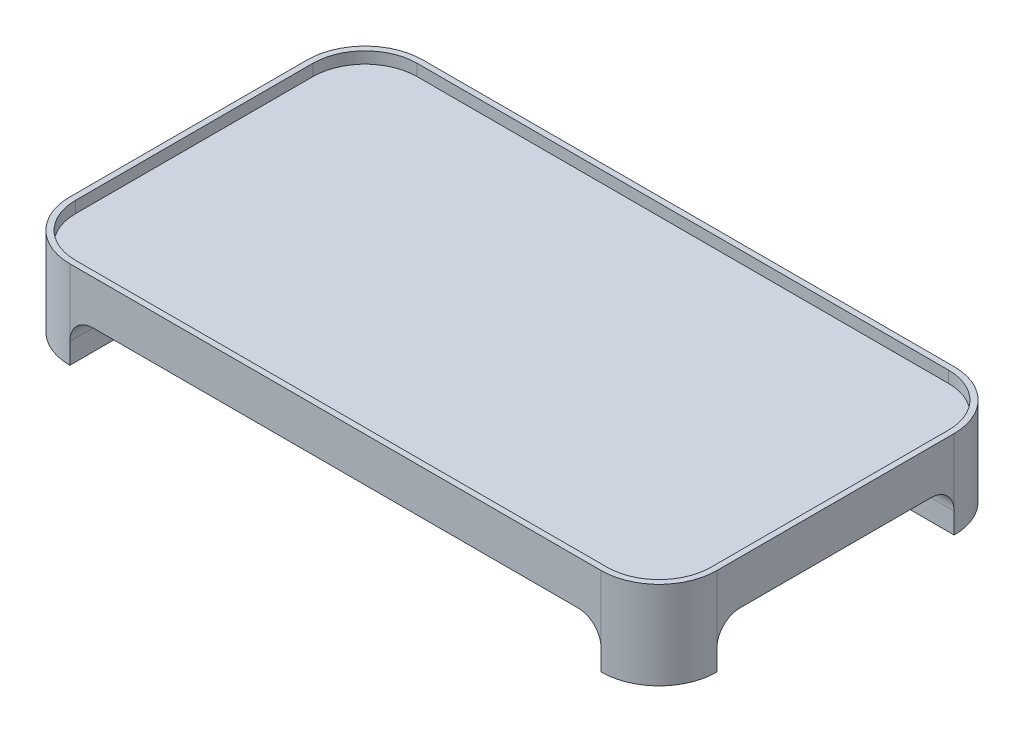
SolidWorks part; units mm, degrees
ref_plane "Front Plane" through (0, 0, 0) normal (0, 0, 1) x (1, 0, 0)
ref_plane "Top Plane" through (0, 0, 0) normal (0, 1, 0) x (1, 0, 0)
ref_plane "Right Plane" through (0, 0, 0) normal (1, 0, 0) x (0, 0, -1)
sketch "Sketch1" plane through (0, 0, 0) normal (0, 1, 0) x (1, 0, 0)
  line L1 (-229.5, 152.5) -> (229.5, 152.5)
  line L2 (-279.5, 102.5) -> (-279.5, -102.5)
  line L3 (-229.5, -152.5) -> (229.5, -152.5)
  line L4 (279.5, 102.5) -> (279.5, -102.5)
  line L5 (-279.5, 152.5) -> (279.5, -152.5) construction
  line L6 (-279.5, -152.5) -> (279.5, 152.5) construction
  arc A0 (-229.5, 152.5) -> (-279.5, 102.5) centre (-229.5, 102.5) ccw
  arc A1 (279.5, 102.5) -> (229.5, 152.5) centre (229.5, 102.5) ccw
  arc A2 (279.5, -102.5) -> (229.5, -152.5) centre (229.5, -102.5) cw
  arc A3 (-229.5, -152.5) -> (-279.5, -102.5) centre (-229.5, -102.5) cw
  point P0 (0, 0)
  dimension "D3" = 50
  dimension "D1" = 305
  dimension "D2" = 559
extrude "Boss-Extrude1" add sketch "Sketch1" along normal blind 76
sketch "Sketch3" plane through (0, 76, 0) normal (0, 1, 0) x (1, 0, 0)
  line L0 (-274.5, 102.5) -> (-274.5, -102.5)
  line L1 (-229.5, -147.5) -> (229.5, -147.5)
  line L2 (274.5, -102.5) -> (274.5, 102.5)
  line L3 (229.5, 147.5) -> (-229.5, 147.5)
  line L4 (-279.5, 102.5) -> (-279.5, -102.5)
  line L5 (-229.5, -152.5) -> (229.5, -152.5)
  line L6 (279.5, -102.5) -> (279.5, 102.5)
  line L7 (229.5, 152.5) -> (-229.5, 152.5)
  line L8 (-279.5, 102.5) -> (-279.5, -102.5) construction
  line L9 (-229.5, -152.5) -> (229.5, -152.5) construction
  line L10 (279.5, -102.5) -> (279.5, 102.5) construction
  line L11 (229.5, 152.5) -> (-229.5, 152.5) construction
  arc A0 (-274.5, -102.5) -> (-229.5, -147.5) centre (-229.5, -102.5) ccw
  arc A1 (229.5, -147.5) -> (274.5, -102.5) centre (229.5, -102.5) ccw
  arc A2 (274.5, 102.5) -> (229.5, 147.5) centre (229.5, 102.5) ccw
  arc A3 (-229.5, 147.5) -> (-274.5, 102.5) centre (-229.5, 102.5) ccw
  arc A4 (-229.5, 152.5) -> (-279.5, 102.5) centre (-229.5, 102.5) ccw
  arc A5 (-279.5, -102.5) -> (-229.5, -152.5) centre (-229.5, -102.5) ccw
  arc A6 (229.5, -152.5) -> (279.5, -102.5) centre (229.5, -102.5) ccw
  arc A7 (279.5, 102.5) -> (229.5, 152.5) centre (229.5, 102.5) ccw
  arc A8 (-229.5, 152.5) -> (-279.5, 102.5) centre (-229.5, 102.5) ccw construction
  arc A9 (-279.5, -102.5) -> (-229.5, -152.5) centre (-229.5, -102.5) ccw construction
  arc A10 (229.5, -152.5) -> (279.5, -102.5) centre (229.5, -102.5) ccw construction
  arc A11 (279.5, 102.5) -> (229.5, 152.5) centre (229.5, 102.5) ccw construction
  dimension "D1" = 0
  dimension "D2" = 5
extrude "Cut-Extrude1" cut sketch "Sketch3" against normal blind 10
sketch "Sketch4" plane through (0, 0, 152.5) normal (0, 0, 1) x (1, 0, 0)
  line L2 (-229.5, 0) -> (-229.5, 18)
  line L3 (-229.5, 76) -> (-229.5, 0) construction
  line L4 (-209.5, 38) -> (209.5, 38)
  line L5 (229.5, 76) -> (229.5, 0) construction
  line L6 (229.5, 18) -> (229.5, 0)
  line L12 (-229.5, 0) -> (229.5, 0)
  arc A0 (229.5, 18) -> (209.5, 38) centre (209.5, 18) ccw
  arc A1 (-229.5, 18) -> (-209.5, 38) centre (-209.5, 18) cw
  point P23 (229.5, 38)
  point P26 (-229.5, 38)
  dimension "D1" = 20
extrude "Cut-Extrude2" cut sketch "Sketch4" against normal through all
sketch "Sketch5" plane through (-279.5, 0, 0) normal (-1, 0, 0) x (0, 0, 1)
  line L0 (-102.5, 0) -> (-102.5, 18)
  line L1 (-102.5, 76) -> (-102.5, 0) construction
  line L2 (-82.5, 38) -> (82.5, 38)
  line L3 (102.5, 76) -> (102.5, 0) construction
  line L4 (102.5, 18) -> (102.5, 0)
  line L5 (102.5, 0) -> (-102.5, 0)
  arc A0 (102.5, 18) -> (82.5, 38) centre (82.5, 18) ccw
  arc A1 (-102.5, 18) -> (-82.5, 38) centre (-82.5, 18) cw
  point P12 (102.5, 38)
  point P15 (-102.5, 38)
  dimension "D1" = 20
extrude "Cut-Extrude3" cut sketch "Sketch5" against normal through all
